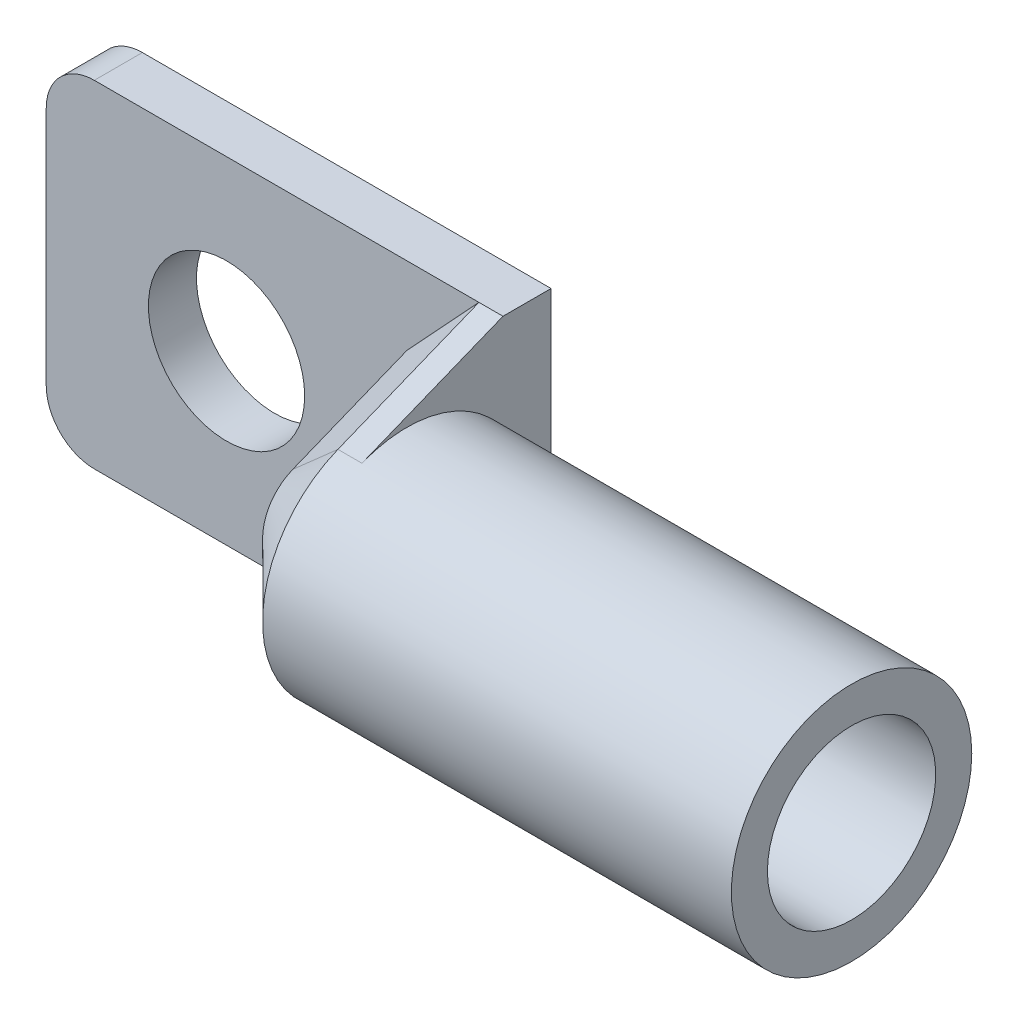
SolidWorks part; units mm, degrees
ref_plane "Front Plane" through (0, 0, 0) normal (0, 0, 1) x (1, 0, 0)
ref_plane "Top Plane" through (0, 0, 0) normal (0, 1, 0) x (1, 0, 0)
ref_plane "Right Plane" through (0, 0, 0) normal (1, 0, 0) x (0, 0, -1)
sketch "Sketch1" plane through (0, 0, 0) normal (0, 0, 1) x (1, 0, 0)
  line L0 (-7.5, 0) -> (7.5, 0) construction
  line L1 (-7.5, 7) -> (7.5, 7)
  line L2 (-7.5, 7) -> (-7.5, -7)
  line L3 (-7.5, -7) -> (7.5, -7)
  line L4 (7.5, 7) -> (7.5, -7)
  circle A0 centre (0, 0) radius 3.25
  dimension "D1" = 6.5
  dimension "D2" = 7.5
  dimension "D3" = 14
extrude "Boss-Extrude1" add sketch "Sketch1" along normal blind 2
sketch "Sketch2" plane through (7.5, 0, 0) normal (1, 0, 0) x (0, 0, -1)
  line L0 (-6, 0) -> (0, 0) construction
  circle A0 centre (-6, 0) radius 3.5
  circle A1 centre (-6, 0) radius 5
  dimension "D1" = 7
  dimension "D2" = 10
  dimension "D3" = 6
extrude "Boss-Extrude2" add sketch "Sketch2" along normal blind 22.5 separate body
sketch "Sketch3" plane through (7.5, 0, 0) normal (1, 0, 0) x (0, 0, -1)
  line L0 (-7.8671, 4.6383) -> (-2, 7)
  line L1 (-2, 7) -> (0, 7)
  line L2 (0, -7) -> (0, 7) construction
  line L3 (0, 7) -> (0, -7)
  line L4 (0, -7) -> (-2, -7)
  line L5 (-2, -7) -> (-7.8671, -4.6383)
  circle A1 centre (-6, 0) radius 5
  arc A2 (-7.8671, 4.6383) -> (-7.8671, -4.6383) centre (-6, 0) ccw
  dimension "D1" = 0
extrude "Boss-Extrude3" add sketch "Sketch3" along normal blind 4
chamfer "Chamfer1" distance 3 angle 45 3 edges at (7.5, 5.8192, 4.9335) (7.5, -5.8192, 4.9335) (7.5, 0, 11)
fillet "Fillet1" radius 2 2 edges at (-7.5, -7, 1) (-7.5, 7, 1)
